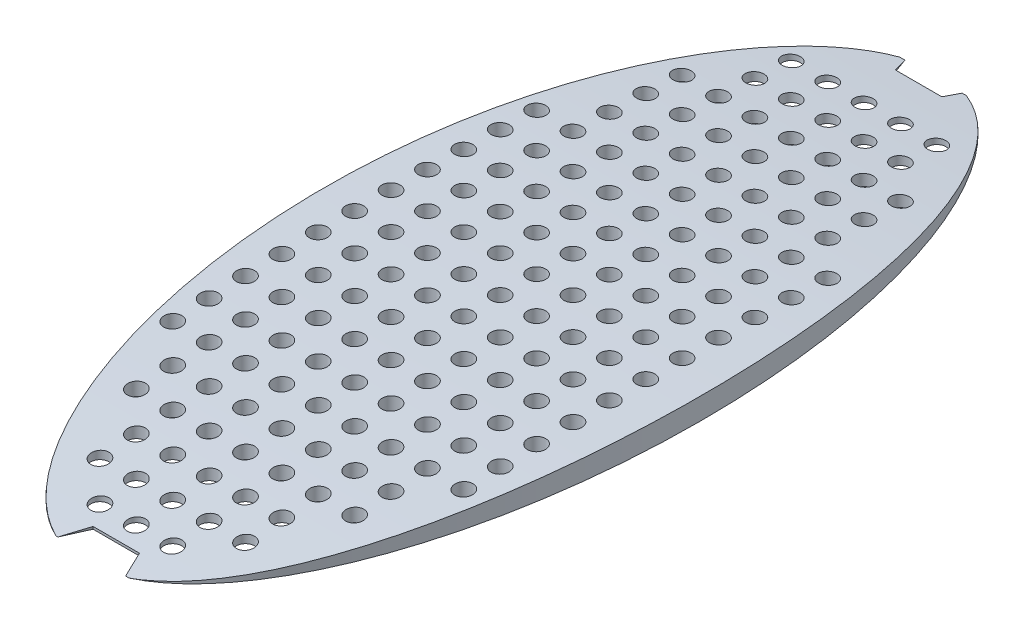
SolidWorks part; units mm, degrees
ref_plane "Alzado" through (0, 0, 0) normal (0, 0, 1) x (1, 0, 0)
ref_plane "Planta" through (0, 0, 0) normal (0, 1, 0) x (1, 0, 0)
ref_plane "Vista lateral" through (0, 0, 0) normal (1, 0, 0) x (0, 0, -1)
sketch "Croquis1" plane through (0, 0, 0) normal (0, 1, 0) x (1, 0, 0)
  line L0 (7.9744, 110.6729) -> (-4.7794, 110.6729)
  line L1 (-4.7794, 110.6729) -> (-6.4204, 115.2474)
  line L2 (-9.2264, -115.3593) -> (-6.1534, -108.4744)
  line L3 (-6.1534, -108.4744) -> (6.5966, -108.4744)
  line L4 (6.5966, -108.4744) -> (9.6083, -115.5073)
  line L5 (9.6047, 115.1509) -> (7.9744, 110.6729)
  line L6 (1.5975, 110.6729) -> (0.2216, -108.4744) construction
  ellipse E0 centre (0.9096, -0.4008) end of major axis (0.2216, -117.4744) minor radius 50.6591 (-6.4204, 115.2474) -> (-9.2264, -115.3593) ccw
  ellipse E1 centre (0.9096, -0.4008) end of major axis (0.2216, -117.4744) minor radius 50.6591 (9.6083, -115.5073) -> (9.6047, 115.1509) ccw
  point P20 (0, 0)
  point P21 (0, 0)
  point P22 (0, 0)
  point P23 (0, 0)
  point P24 (0, 0)
  point P25 (0, 0)
  dimension "D1" = 219.1473
sketch "Croquis2" plane through (0, 0, 0) normal (1, 0, 0) x (0, 0, -1)
  line L0 (115.2474, 0) -> (-115.3593, 0) construction
  line L1 (-115.1393, 0) -> (114.744, 0)
  arc A0 (-115.1393, 0) -> (114.744, 0) centre (-0.1976, -1108.4568) cw
extrude "Saliente-Extruir1" add sketch "Croquis1" along normal blind 10
extrude "Cortar-Extruir1" cut sketch "Croquis2" against normal through all both and the other way through all flip side to cut contours A0 L1
sketch "Croquis3" plane through (0, 0, 0) normal (0, -1, 0) x (1, 0, 0)
  line L0 (0, -3.2689) -> (0, 3.2689) construction
  circle A0 centre (0, 102.7365) radius 2.5
  circle A1 centre (0, 92.7365) radius 2.5
  circle A2 centre (0, 82.7365) radius 2.5
  circle A3 centre (0, 72.7365) radius 2.5
  circle A4 centre (0, 62.7365) radius 2.5
  circle A5 centre (0, 52.7365) radius 2.5
  circle A6 centre (0, 42.7365) radius 2.5
  circle A7 centre (0, 32.7365) radius 2.5
  circle A8 centre (0, 22.7365) radius 2.5
  circle A9 centre (0, 12.7365) radius 2.5
  circle A10 centre (0, 2.7365) radius 2.5
  circle A11 centre (0, -7.2635) radius 2.5
  circle A12 centre (0, -17.2635) radius 2.5
  circle A13 centre (0, -27.2635) radius 2.5
  circle A14 centre (0, -37.2635) radius 2.5
  circle A15 centre (0, -47.2635) radius 2.5
  circle A16 centre (0, -57.2635) radius 2.5
  circle A17 centre (0, -67.2635) radius 2.5
  circle A18 centre (0, -77.2635) radius 2.5
  circle A19 centre (0, -87.2635) radius 2.5
  circle A20 centre (0, -97.2635) radius 2.5
  circle A21 centre (10, 92.7365) radius 2.5
  circle A22 centre (10, 82.7365) radius 2.5
  circle A23 centre (10, 72.7365) radius 2.5
  circle A24 centre (10, 62.7365) radius 2.5
  circle A25 centre (10, 52.7365) radius 2.5
  circle A26 centre (10, 42.7365) radius 2.5
  circle A27 centre (10, 32.7365) radius 2.5
  circle A28 centre (10, 22.7365) radius 2.5
  circle A29 centre (10, 12.7365) radius 2.5
  circle A30 centre (10, 2.7365) radius 2.5
  circle A31 centre (10, -7.2635) radius 2.5
  circle A32 centre (10, -17.2635) radius 2.5
  circle A33 centre (10, -27.2635) radius 2.5
  circle A34 centre (10, -37.2635) radius 2.5
  circle A35 centre (10, -47.2635) radius 2.5
  circle A36 centre (10, -57.2635) radius 2.5
  circle A37 centre (10, -67.2635) radius 2.5
  circle A38 centre (10, -77.2635) radius 2.5
  circle A39 centre (10, -87.2635) radius 2.5
  circle A40 centre (10, -97.2635) radius 2.5
  circle A41 centre (20, 92.7365) radius 2.5
  circle A42 centre (20, 82.7365) radius 2.5
  circle A43 centre (20, 72.7365) radius 2.5
  circle A44 centre (20, 62.7365) radius 2.5
  circle A45 centre (20, 52.7365) radius 2.5
  circle A46 centre (20, 42.7365) radius 2.5
  circle A47 centre (20, 32.7365) radius 2.5
  circle A48 centre (20, 22.7365) radius 2.5
  circle A49 centre (20, 12.7365) radius 2.5
  circle A50 centre (20, 2.7365) radius 2.5
  circle A51 centre (20, -7.2635) radius 2.5
  circle A52 centre (20, -17.2635) radius 2.5
  circle A53 centre (20, -27.2635) radius 2.5
  circle A54 centre (20, -37.2635) radius 2.5
  circle A55 centre (20, -47.2635) radius 2.5
  circle A56 centre (20, -57.2635) radius 2.5
  circle A57 centre (20, -67.2635) radius 2.5
  circle A58 centre (20, -77.2635) radius 2.5
  circle A59 centre (20, -87.2635) radius 2.5
  circle A60 centre (20, -97.2635) radius 2.5
  circle A63 centre (30, 72.7365) radius 2.5
  circle A64 centre (30, 62.7365) radius 2.5
  circle A65 centre (30, 52.7365) radius 2.5
  circle A66 centre (30, 42.7365) radius 2.5
  circle A67 centre (30, 32.7365) radius 2.5
  circle A68 centre (30, 22.7365) radius 2.5
  circle A69 centre (30, 12.7365) radius 2.5
  circle A70 centre (30, 2.7365) radius 2.5
  circle A71 centre (30, -7.2635) radius 2.5
  circle A72 centre (30, -17.2635) radius 2.5
  circle A73 centre (30, -27.2635) radius 2.5
  circle A74 centre (30, -37.2635) radius 2.5
  circle A75 centre (30, -47.2635) radius 2.5
  circle A76 centre (30, -57.2635) radius 2.5
  circle A77 centre (30, -67.2635) radius 2.5
  circle A78 centre (30, -77.2635) radius 2.5
  circle A85 centre (40, 52.7365) radius 2.5
  circle A86 centre (40, 42.7365) radius 2.5
  circle A87 centre (40, 32.7365) radius 2.5
  circle A88 centre (40, 22.7365) radius 2.5
  circle A89 centre (40, 12.7365) radius 2.5
  circle A90 centre (40, 2.7365) radius 2.5
  circle A91 centre (40, -7.2635) radius 2.5
  circle A92 centre (40, -17.2635) radius 2.5
  circle A93 centre (40, -27.2635) radius 2.5
  circle A94 centre (40, -37.2635) radius 2.5
  circle A95 centre (40, -47.2635) radius 2.5
  circle A101 centre (10, 102.7365) radius 2.5
  circle A105 centre (-10, 102.7365) radius 2.5
  circle A106 centre (-40, -47.2635) radius 2.5
  circle A107 centre (-40, -37.2635) radius 2.5
  circle A108 centre (-40, -27.2635) radius 2.5
  circle A109 centre (-40, -17.2635) radius 2.5
  circle A110 centre (-40, -7.2635) radius 2.5
  circle A111 centre (-40, 2.7365) radius 2.5
  circle A112 centre (-40, 12.7365) radius 2.5
  circle A113 centre (-40, 22.7365) radius 2.5
  circle A114 centre (-40, 32.7365) radius 2.5
  circle A115 centre (-40, 42.7365) radius 2.5
  circle A116 centre (-40, 52.7365) radius 2.5
  circle A117 centre (-30, -77.2635) radius 2.5
  circle A118 centre (-30, -67.2635) radius 2.5
  circle A119 centre (-30, -57.2635) radius 2.5
  circle A120 centre (-30, -47.2635) radius 2.5
  circle A121 centre (-30, -37.2635) radius 2.5
  circle A122 centre (-30, -27.2635) radius 2.5
  circle A123 centre (-30, -17.2635) radius 2.5
  circle A124 centre (-30, -7.2635) radius 2.5
  circle A125 centre (-30, 2.7365) radius 2.5
  circle A126 centre (-30, 12.7365) radius 2.5
  circle A127 centre (-30, 22.7365) radius 2.5
  circle A128 centre (-30, 32.7365) radius 2.5
  circle A129 centre (-30, 42.7365) radius 2.5
  circle A130 centre (-30, 52.7365) radius 2.5
  circle A131 centre (-30, 62.7365) radius 2.5
  circle A132 centre (-30, 72.7365) radius 2.5
  circle A133 centre (-20, -97.2635) radius 2.5
  circle A134 centre (-20, -87.2635) radius 2.5
  circle A135 centre (-20, -77.2635) radius 2.5
  circle A136 centre (-20, -67.2635) radius 2.5
  circle A137 centre (-20, -57.2635) radius 2.5
  circle A138 centre (-20, -47.2635) radius 2.5
  circle A139 centre (-20, -37.2635) radius 2.5
  circle A140 centre (-20, -27.2635) radius 2.5
  circle A141 centre (-20, -17.2635) radius 2.5
  circle A142 centre (-20, -7.2635) radius 2.5
  circle A143 centre (-20, 2.7365) radius 2.5
  circle A144 centre (-20, 12.7365) radius 2.5
  circle A145 centre (-20, 22.7365) radius 2.5
  circle A146 centre (-20, 32.7365) radius 2.5
  circle A147 centre (-20, 42.7365) radius 2.5
  circle A148 centre (-20, 52.7365) radius 2.5
  circle A149 centre (-20, 62.7365) radius 2.5
  circle A150 centre (-20, 72.7365) radius 2.5
  circle A151 centre (-20, 82.7365) radius 2.5
  circle A152 centre (-20, 92.7365) radius 2.5
  circle A153 centre (-10, -97.2635) radius 2.5
  circle A154 centre (-10, -87.2635) radius 2.5
  circle A155 centre (-10, -77.2635) radius 2.5
  circle A156 centre (-10, -67.2635) radius 2.5
  circle A157 centre (-10, -57.2635) radius 2.5
  circle A158 centre (-10, -47.2635) radius 2.5
  circle A159 centre (-10, -37.2635) radius 2.5
  circle A160 centre (-10, -27.2635) radius 2.5
  circle A161 centre (-10, -17.2635) radius 2.5
  circle A162 centre (-10, -7.2635) radius 2.5
  circle A163 centre (-10, 2.7365) radius 2.5
  circle A164 centre (-10, 12.7365) radius 2.5
  circle A165 centre (-10, 22.7365) radius 2.5
  circle A166 centre (-10, 32.7365) radius 2.5
  circle A167 centre (-10, 42.7365) radius 2.5
  circle A168 centre (-10, 52.7365) radius 2.5
  circle A169 centre (-10, 62.7365) radius 2.5
  circle A170 centre (-10, 72.7365) radius 2.5
  circle A171 centre (-10, 82.7365) radius 2.5
  circle A172 centre (-10, 92.7365) radius 2.5
  point P2 (0, 0)
  point P3 (0, 0)
  point P164 (0, 0)
  dimension "D1" = 5
extrude "Cortar-Extruir2" cut sketch "Croquis3" against normal through all both and the other way through all
